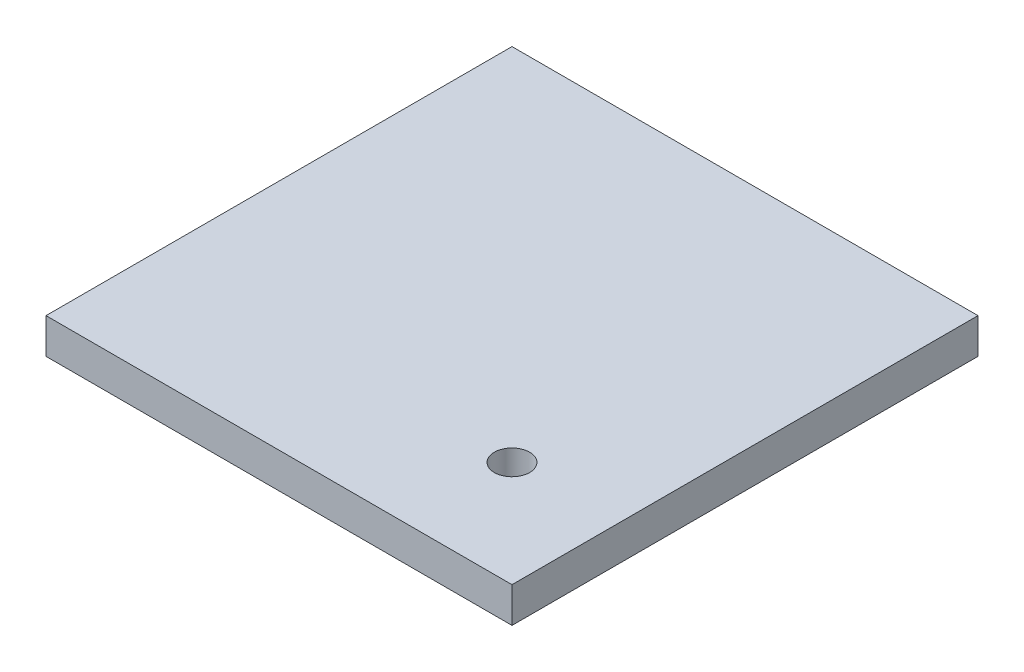
SolidWorks part; units mm, degrees
ref_plane "Ön Düzlem" through (0, 0, 0) normal (0, 0, 1) x (1, 0, 0)
ref_plane "Üst Düzlem" through (0, 0, 0) normal (0, 1, 0) x (1, 0, 0)
ref_plane "Sağ Düzlem" through (0, 0, 0) normal (1, 0, 0) x (0, 0, -1)
sketch "Çizim1" plane through (0, 0, 0) normal (0, 1, 0) x (1, 0, 0)
  line L1 (0, 0) -> (66, 0)
  line L2 (0, 0) -> (0, 66)
  line L3 (0, 66) -> (66, 66)
  line L4 (66, 0) -> (66, 66)
  circle A0 centre (51, 15) radius 2.5
  dimension "D3" = 5
  dimension "D4" = 15
  dimension "D5" = 15
  dimension "D1" = 66
  dimension "D2" = 66
extrude "Yükseklik-Ekstrüzyon1" add sketch "Çizim1" along normal blind 5
